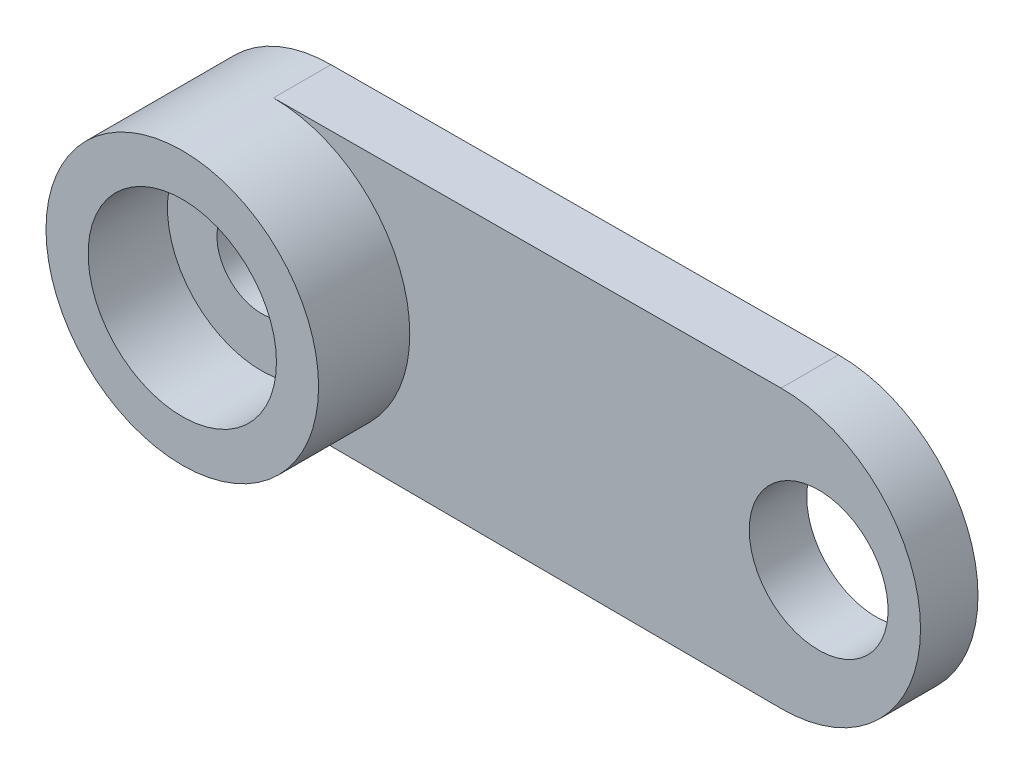
SolidWorks part; units mm, degrees
ref_plane "Front Plane" through (0, 0, 0) normal (0, 0, 1) x (1, 0, 0)
ref_plane "Top Plane" through (0, 0, 0) normal (0, 1, 0) x (1, 0, 0)
ref_plane "Right Plane" through (0, 0, 0) normal (1, 0, 0) x (0, 0, -1)
sketch "Sketch2" plane through (0, 0, 0) normal (0, 0, 1) x (1, 0, 0)
  circle A0 centre (0, 0) radius 3.4925
  dimension "D1" = 6.985
extrude "Boss-Extrude1" add sketch "Sketch2" along normal blind 3.81 contours A0
sketch "Sketch3" plane through (0, 0, 3.81) normal (0, 0, 1) x (1, 0, 0)
  circle A0 centre (0, 0) radius 2.413
  dimension "D1" = 4.826
extrude "Cut-Extrude1" cut sketch "Sketch3" against normal blind 2.032
sketch "Sketch4" plane through (0, 0, 1.778) normal (0, 0, 1) x (1, 0, 0)
  circle A0 centre (0, 0) radius 1.143
  dimension "D1" = 2.286
extrude "Cut-Extrude2" cut sketch "Sketch4" against normal blind 2.2225
sketch "Sketch5" plane through (0, 0, 0) normal (0, 0, -1) x (-1, 0, 0)
  circle A0 centre (0, 0) radius 2.286
  dimension "D1" = 4.572
extrude "Cut-Extrude3" cut sketch "Sketch5" against normal blind 1.016
sketch "Sketch6" plane through (0, 0, 0) normal (0, 0, -1) x (-1, 0, 0)
  line L0 (0, 3.4925) -> (-13.0068, 3.556)
  line L1 (-13.0068, -3.556) -> (0, -3.4925)
  circle A0 centre (-13.97, 0) radius 1.778
  circle A2 centre (0, 0) radius 3.4925 construction
  arc A3 (-13.0068, 3.556) -> (-13.0068, -3.556) centre (-13.0242, 0) ccw
  arc A4 (0, 3.4925) -> (0, -3.4925) centre (0, 0) ccw
  point P11 (0, 0)
  point P12 (0, 0)
  point P17 (0, 3.4925)
  dimension "D1" = 13.97
  dimension "D2" = 3.556
  dimension "D3" = 3.556
  dimension "D5" = 13.0068
extrude "Boss-Extrude2" add sketch "Sketch6" against normal blind 1.4732
